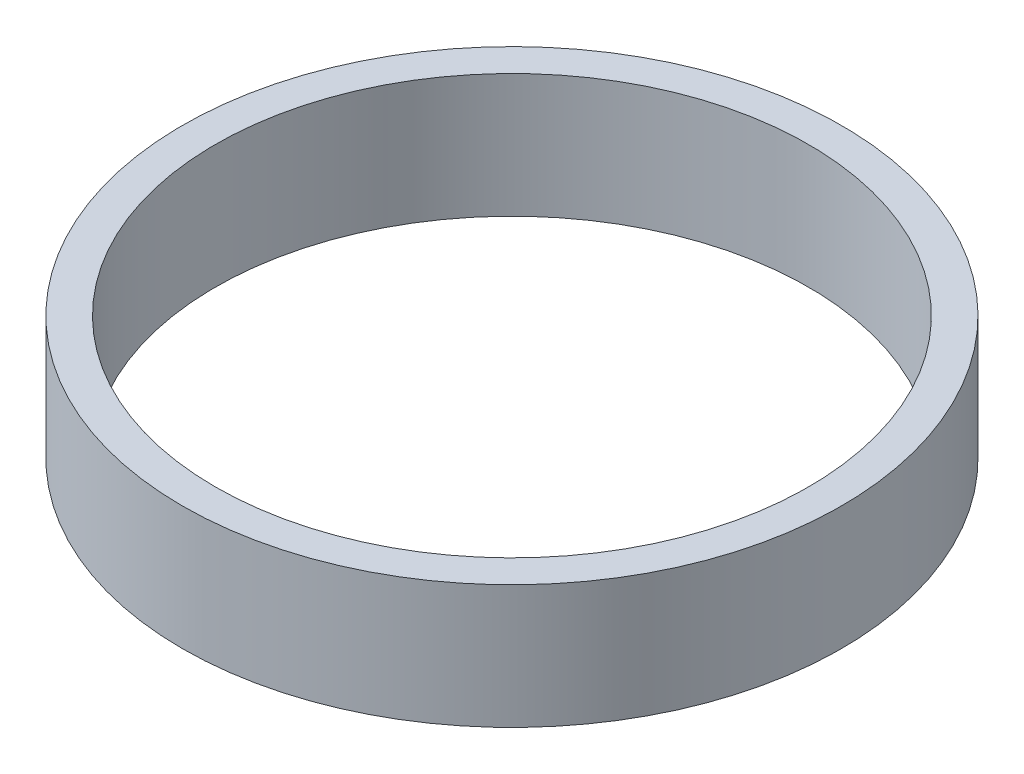
SolidWorks part; units mm, degrees
ref_plane "Front Plane" through (0, 0, 0) normal (0, 0, 1) x (1, 0, 0)
ref_plane "Top Plane" through (0, 0, 0) normal (0, 1, 0) x (1, 0, 0)
ref_plane "Right Plane" through (0, 0, 0) normal (1, 0, 0) x (0, 0, -1)
sketch "Sketch1" plane through (0, 0, 0) normal (0, 1, 0) x (1, 0, 0)
  circle A0 centre (0, 0) radius 36
  circle A1 centre (0, 0) radius 40
  dimension "D1" = 80
  dimension "D2" = 4
extrude "Boss-Extrude1" add sketch "Sketch1" along normal blind 15
